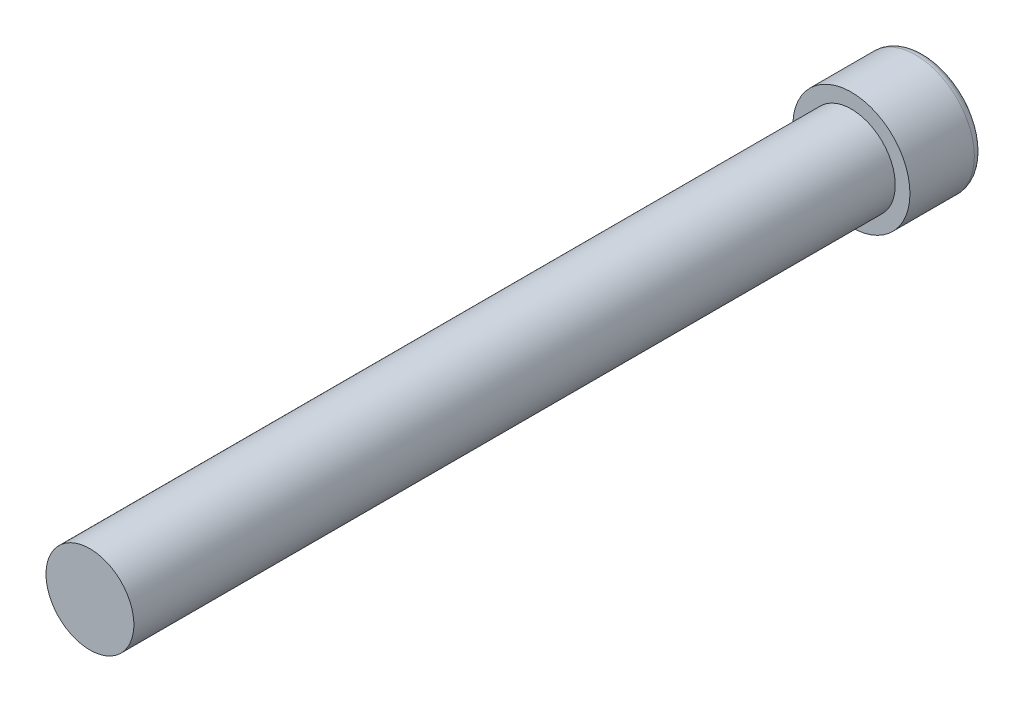
SolidWorks part; units mm, degrees
ref_plane "Plan1" through (0, 0, 0) normal (0, 0, 1) x (1, 0, 0)
ref_plane "Plan2" through (0, 0, 0) normal (0, 1, 0) x (1, 0, 0)
ref_plane "Plan3" through (0, 0, 0) normal (1, 0, 0) x (0, 0, -1)
sketch "Esquisse1" plane through (0, 0, 0) normal (0, 0, 1) x (1, 0, 0)
  circle A0 centre (0, 0) radius 2
  dimension "D1" = 4
extrude "Base-Extrusion" add sketch "Esquisse1" along normal blind 2.5
sketch "Esquisse2" plane through (0, 0, 2.5) normal (0, 0, 1) x (1, 0, 0)
  circle A0 centre (0, 0) radius 1.5
extrude "Boss.-Extru.1" add sketch "Esquisse2" along normal blind 26
fillet "Congé1" radius 0.3 1 edges at (2, 0, 0)
sketch "Esquisse3" plane through (0, 0, 0) normal (0, 0, -1) x (-1, 0, 0)
  line L1 (1.5358, 0) -> (0.7679, 1.33)
  line L2 (0.7679, 1.33) -> (-0.7679, 1.33)
  line L3 (-0.7679, 1.33) -> (-1.5358, 0)
  line L4 (-1.5358, 0) -> (-0.7679, -1.33)
  line L5 (-0.7679, -1.33) -> (0.7679, -1.33)
  line L6 (0.7679, -1.33) -> (1.5358, 0)
  circle A0 centre (0, 0) radius 1.33 construction
  dimension "D1" = 2.66
extrude "Enlèv. mat.-Extru.1" cut sketch "Esquisse3" against normal blind 2
